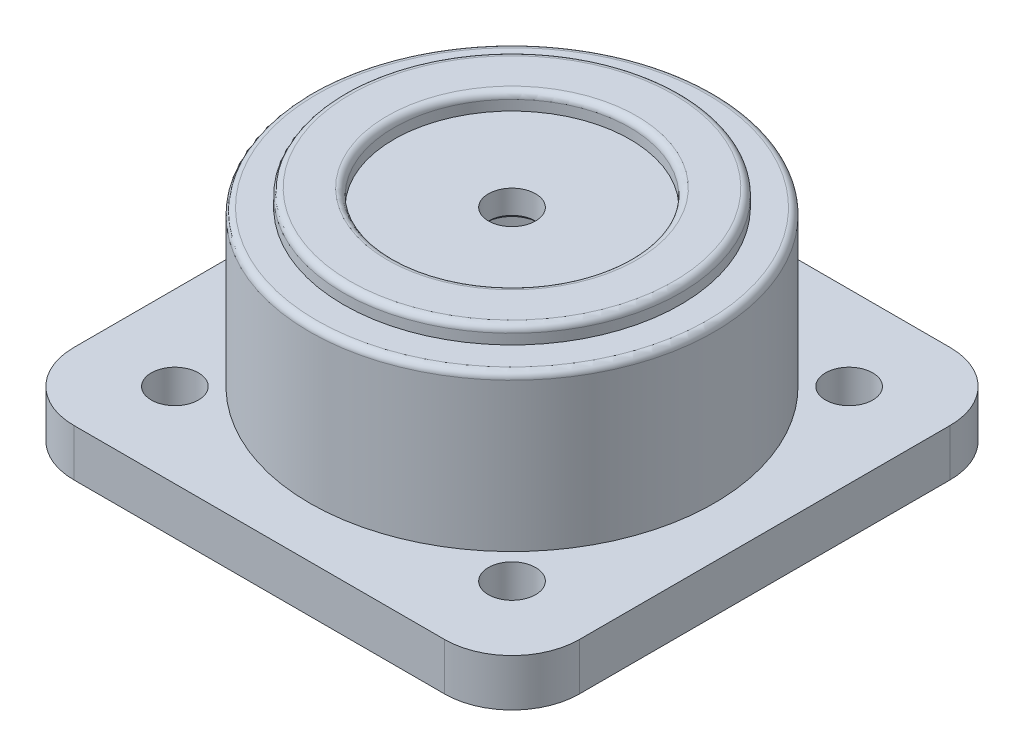
SolidWorks part; units mm, degrees
ref_plane "前视基准面" through (0, 0, 0) normal (0, 0, 1) x (1, 0, 0)
ref_plane "上视基准面" through (0, 0, 0) normal (0, 1, 0) x (1, 0, 0)
ref_plane "右视基准面" through (0, 0, 0) normal (1, 0, 0) x (0, 0, -1)
other "Configuration Table"
sketch "草图1" plane through (0, 0, 0) normal (0, 1, 0) x (1, 0, 0)
  circle A0 centre (0, 0) radius 30
  dimension "D1" = 60
extrude "凸台-拉伸1" add sketch "草图1" along normal blind 30
sketch "草图2" plane through (0, 0, 0) normal (0, -1, 0) x (1, 0, 0)
  line L1 (-27.5, -37.5) -> (27.5, -37.5)
  line L2 (-37.5, -27.5) -> (-37.5, 27.5)
  line L3 (-27.5, 37.5) -> (27.5, 37.5)
  line L4 (37.5, -27.5) -> (37.5, 27.5)
  line L5 (-37.5, -37.5) -> (37.5, 37.5) construction
  line L6 (-37.5, 37.5) -> (37.5, -37.5) construction
  arc A1 (37.5, 27.5) -> (27.5, 37.5) centre (27.5, 27.5) ccw
  arc A2 (37.5, -27.5) -> (27.5, -37.5) centre (27.5, -27.5) cw
  arc A3 (-27.5, -37.5) -> (-37.5, -27.5) centre (-27.5, -27.5) cw
  arc A4 (-27.5, 37.5) -> (-37.5, 27.5) centre (-27.5, 27.5) ccw
  circle A5 centre (-25, 25) radius 3.5
  circle A6 centre (-25, -25) radius 3.5
  circle A7 centre (25, 25) radius 3.5
  circle A8 centre (25, -25) radius 3.5
  point P0 (0, 0)
  dimension "D3" = 10
  dimension "D4" = 50
  dimension "D5" = 50
  dimension "D6" = 50
  dimension "D7" = 50
  dimension "D8" = 7
  dimension "D9" = 7
  dimension "D10" = 7
  dimension "D11" = 7
  dimension "D12" = 75
  dimension "D2" = 75
extrude "凸台-拉伸2" add sketch "草图2" against normal blind 7
sketch "草图3" plane through (0, 0, 0) normal (0, -1, 0) x (1, 0, 0)
  circle A0 centre (0, 0) radius 24
  dimension "D1" = 48
extrude "切除-拉伸1" cut sketch "草图3" against normal offset from surface (26 mm away) 4 up to face at (0, 30, 30)
sketch "草图4" plane through (0, 26, 0) normal (0, -1, 0) x (1, 0, 0)
  circle A0 centre (0, 0) radius 3.5
  dimension "D1" = 7
extrude "切除-拉伸2" cut sketch "草图4" against normal through all
sketch "草图5" plane through (0, 26, 0) normal (0, -1, 0) x (1, 0, 0)
  circle A0 centre (0, 0) radius 7.5
  circle A1 centre (0, 0) radius 8.5
  dimension "D1" = 15
  dimension "D2" = 17
extrude "切除-拉伸3" cut sketch "草图5" against normal blind 2.5
chamfer "倒角1" distance 0.5 angle 45 1 edges at (0, 26, -3.5)
sketch "草图10" plane through (0, 0, 0) normal (0, 0, 1) x (1, 0, 0)
  line L1 (-6, 15) -> (6, 15)
  line L2 (-6, 15) -> (-6, 23)
  line L3 (-6, 23) -> (6, 23)
  line L4 (6, 15) -> (6, 23)
  line L5 (0, 30) -> (0, 7) construction
  line L6 (30, 7) -> (-30, 7) construction
  dimension "D1" = 12
  dimension "D2" = 6
  dimension "D3" = 8
  dimension "D4" = 8
extrude "切除-拉伸4" cut sketch "草图10" against normal blind 49
sketch "草图11" plane through (0, 30, 0) normal (0, 1, 0) x (1, 0, 0)
  circle A0 centre (0, 0) radius 25
  circle A1 centre (0, 0) radius 17.5
  dimension "D1" = 35
  dimension "D2" = 50
extrude "凸台-拉伸3" add sketch "草图11" along normal blind 2.5
fillet "圆角1" radius 1 3 edges at (0, 30, 30) (0, 32.5, 17.5) (0, 32.5, 25)
